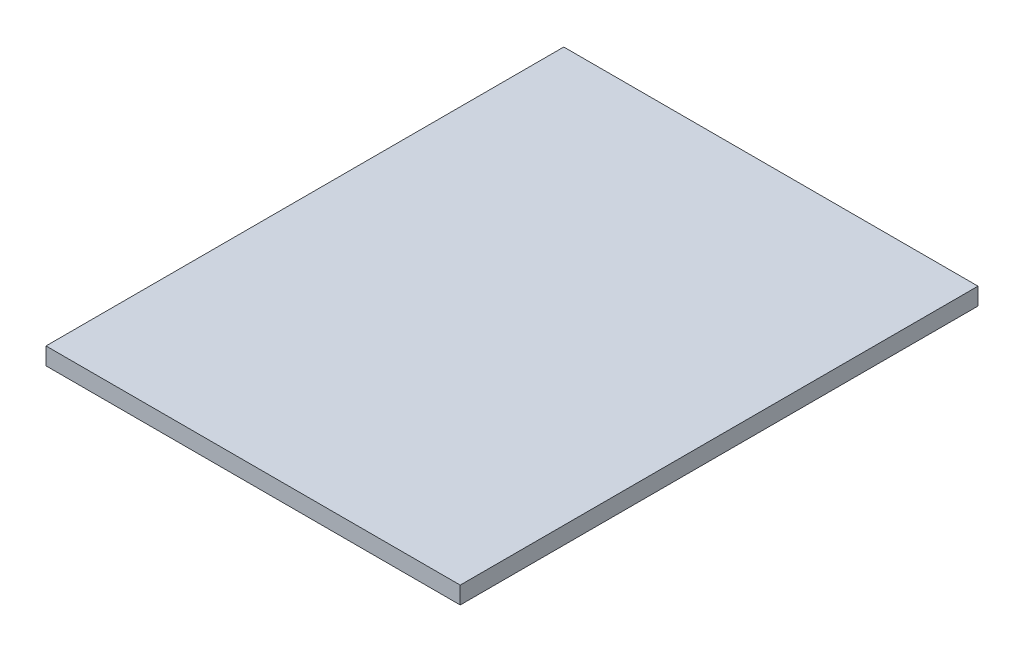
SolidWorks part; units mm, degrees
material "Oak"
ref_plane "Front Plane" through (0, 0, 0) normal (0, 0, 1) x (1, 0, 0)
ref_plane "Top Plane" through (0, 0, 0) normal (0, 1, 0) x (1, 0, 0)
ref_plane "Right Plane" through (0, 0, 0) normal (1, 0, 0) x (0, 0, -1)
sketch "Sketch1" plane through (0, 0, 0) normal (0, 1, 0) x (1, 0, 0)
  line L1 (-60, 75) -> (60, 75)
  line L2 (-60, 75) -> (-60, -75)
  line L3 (-60, -75) -> (60, -75)
  line L4 (60, 75) -> (60, -75)
  line L5 (-60, 75) -> (60, -75) construction
  line L6 (-60, -75) -> (60, 75) construction
  point P0 (0, 0)
  dimension "D1" = 120
  dimension "D2" = 150
extrude "Boss-Extrude1" add sketch "Sketch1" along normal blind 5
